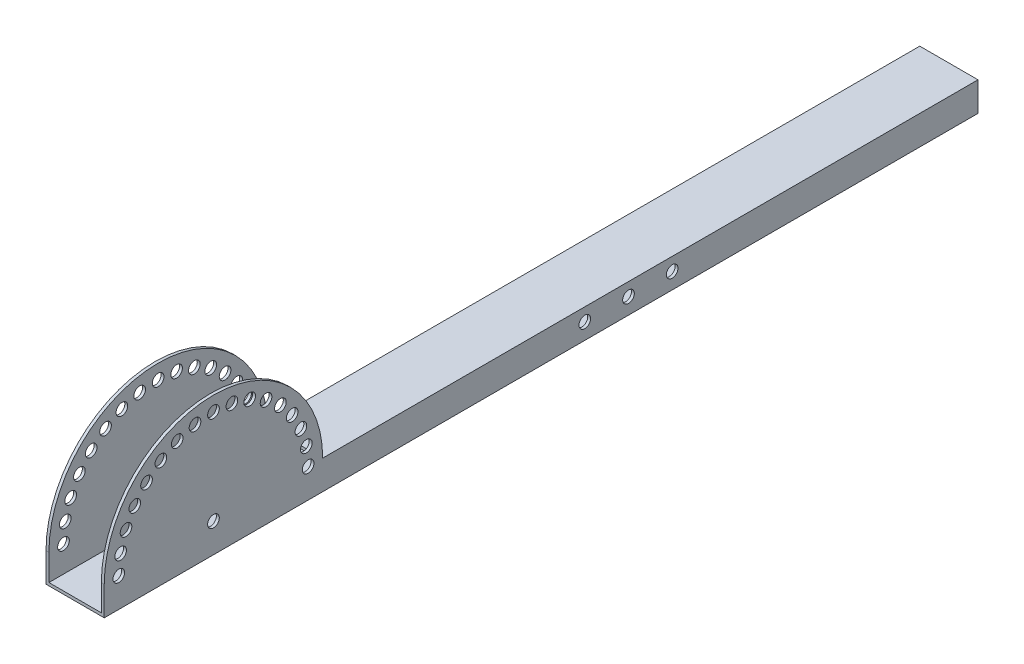
SolidWorks part; units mm, degrees
material "1023 Carbon Steel Sheet (SS)"
ref_plane "Front Plane" through (0, 0, 0) normal (0, 0, 1) x (1, 0, 0)
ref_plane "Top Plane" through (0, 0, 0) normal (0, 1, 0) x (1, 0, 0)
ref_plane "Right Plane" through (0, 0, 0) normal (1, 0, 0) x (0, 0, -1)
sketch "Sketch1" plane through (0, 0, 0) normal (0, 0, 1) x (1, 0, 0)
  line L1 (0, 0) -> (40, 0)
  line L2 (0, 0) -> (0, -20)
  line L3 (0, -20) -> (40, -20)
  line L4 (40, 0) -> (40, -20)
  line L8 (2, -2) -> (2, -18)
  line L9 (2, -18) -> (38, -18)
  line L10 (38, -2) -> (38, -18)
  line L11 (2, -2) -> (38, -2)
  dimension "D1" = 20
  dimension "D2" = 40
  dimension "D3" = 2
extrude "Boss-Extrude1" add sketch "Sketch1" along normal blind 400
sketch "Sketch2" plane through (40, 0, 0) normal (1, 0, 0) x (0, 0, -1)
  line L0 (0, -20) -> (0, 0) construction
  line L1 (-400, -20) -> (0, -20) construction
  circle A0 centre (-10, -9) radius 4
  circle A1 centre (-40, -9) radius 4
  circle A2 centre (-70, -9) radius 4
  dimension "D1" = 8
  dimension "D2" = 8
  dimension "D3" = 10
  dimension "D4" = 30
  dimension "D5" = 11
  dimension "D6" = 11
  dimension "D7" = 8
  dimension "D8" = 11
  dimension "D9" = 30
extrude "Cut-Extrude1" cut sketch "Sketch2" against normal through all
sketch "Sketch3" plane through (40, 0, 0) normal (1, 0, 0) x (0, 0, -1)
  line L0 (-400, 0) -> (0, 0) construction
  line L1 (-400, 0) -> (-250, 0)
  arc A0 (-250, 0) -> (-400, 0) centre (-325, 0) ccw
  dimension "D1" = 150
extrude "Boss-Extrude2" add sketch "Sketch3" against normal blind 2
ref_plane "Plane1" through (20, 0, 0) normal (1, 0, 0) x (0, 0, -1)
mirror "Mirror1" about plane through (20, 0, 0) normal (1, 0, 0) of "Boss-Extrude2"
sketch "Sketch4" plane through (40, 0, 0) normal (1, 0, 0) x (0, 0, -1)
  circle A0 centre (-325, 0) radius 65 construction
  circle A2 centre (-390, 0) radius 4
  circle A3 centre (-388.751, 12.6809) radius 4
  circle A4 centre (-385.0522, 24.8744) radius 4
  circle A5 centre (-379.0455, 36.1121) radius 4
  circle A6 centre (-370.9619, 45.9619) radius 4
  circle A7 centre (-361.1121, 54.0455) radius 4
  circle A8 centre (-349.8744, 60.0522) radius 4
  circle A9 centre (-337.6809, 63.751) radius 4
  circle A10 centre (-325, 65) radius 4
  circle A11 centre (-312.3191, 63.751) radius 4
  circle A12 centre (-300.1256, 60.0522) radius 4
  circle A13 centre (-288.8879, 54.0455) radius 4
  circle A14 centre (-279.0381, 45.9619) radius 4
  circle A15 centre (-270.9545, 36.1121) radius 4
  circle A16 centre (-264.9478, 24.8744) radius 4
  circle A17 centre (-261.249, 12.6809) radius 4
  circle A18 centre (-260, 0) radius 4
  circle A19 centre (-261.249, -12.6809) radius 4 [skipped]
  circle A20 centre (-264.9478, -24.8744) radius 4 [skipped]
  circle A21 centre (-270.9545, -36.1121) radius 4 [skipped]
  circle A22 centre (-279.0381, -45.9619) radius 4 [skipped]
  circle A23 centre (-288.8879, -54.0455) radius 4 [skipped]
  circle A24 centre (-300.1256, -60.0522) radius 4 [skipped]
  circle A25 centre (-312.3191, -63.751) radius 4 [skipped]
  circle A26 centre (-325, -65) radius 4 [skipped]
  circle A27 centre (-337.6809, -63.751) radius 4 [skipped]
  circle A28 centre (-349.8744, -60.0522) radius 4 [skipped]
  circle A29 centre (-361.1121, -54.0455) radius 4 [skipped]
  circle A30 centre (-370.9619, -45.9619) radius 4 [skipped]
  circle A31 centre (-379.0455, -36.1121) radius 4 [skipped]
  circle A32 centre (-385.0522, -24.8744) radius 4 [skipped]
  circle A33 centre (-388.751, -12.6809) radius 4 [skipped]
  dimension "D2" = 8
  dimension "D3" = 32
extrude "Cut-Extrude2" cut sketch "Sketch4" against normal through all
sketch "Sketch5" plane through (40, 0, 0) normal (1, 0, 0) x (0, 0, -1)
  circle A0 centre (-325, 0) radius 4
  dimension "D1" = 8
extrude "Cut-Extrude3" cut sketch "Sketch5" against normal through all
sketch "Sketch7" plane through (0, 0, 0) normal (0, 1, 0) x (1, 0, 0)
  line L0 (2, -250) -> (2, -400)
  line L1 (2, -400) -> (38, -400)
  line L2 (38, -400) -> (38, -250)
  line L3 (38, -250) -> (2, -250)
extrude "Cut-Extrude4" cut sketch "Sketch7" against normal up to next
sketch "Sketch8" plane through (0, 0, 0) normal (0, 0, -1) x (-1, 0, 0)
  line L0 (-40, 0) -> (0, 0)
  line L1 (0, 0) -> (0, -20)
  line L2 (0, -20) -> (-40, -20)
  line L3 (-40, -20) -> (-40, 0)
  line L4 (-38, -2) -> (-2, -2)
  line L5 (-2, -2) -> (-2, -18)
  line L6 (-2, -18) -> (-38, -18)
  line L7 (-38, -18) -> (-38, -2)
extrude "Boss-Extrude3" add sketch "Sketch8" along normal blind 200
